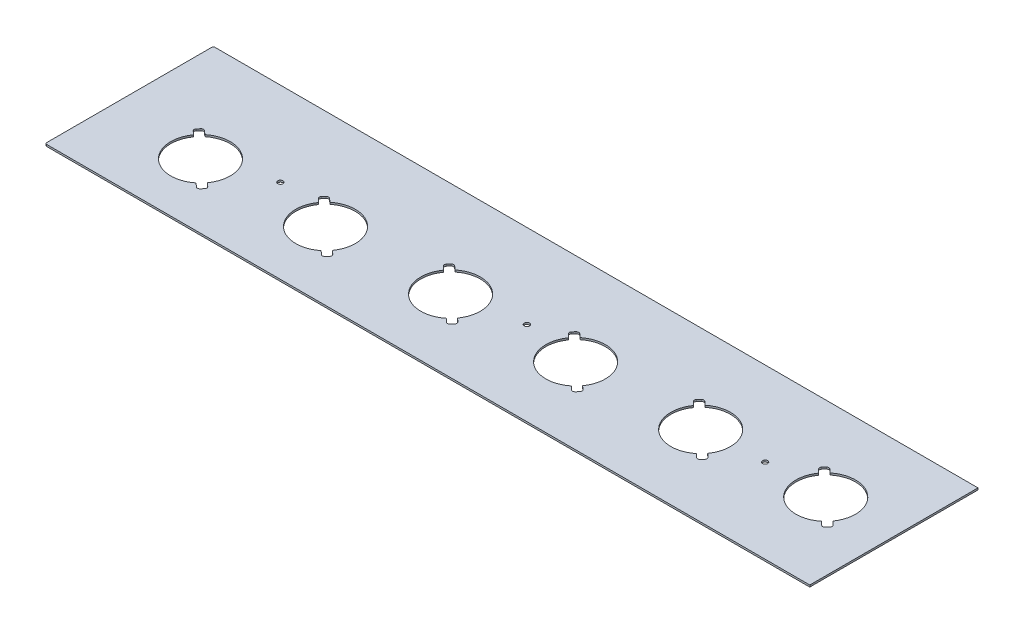
SolidWorks part; units mm, degrees
material "E-Glass Fiber"
ref_plane "Front" through (0, 0, 0) normal (0, 0, 1) x (1, 0, 0)
ref_plane "Top" through (0, 0, 0) normal (0, 1, 0) x (1, 0, 0)
ref_plane "Right" through (0, 0, 0) normal (1, 0, 0) x (0, 0, -1)
sketch "Sketch2" plane through (0, 0, 0) normal (0, 1, 0) x (1, 0, 0)
  line L1 (-317.5, 69.85) -> (317.5, 69.85)
  line L2 (-317.5, 69.85) -> (-317.5, -69.85)
  line L3 (-317.5, -69.85) -> (317.5, -69.85)
  line L5 (317.5, 69.85) -> (317.5, -69.85)
  line L6 (-317.5, 69.85) -> (317.5, -69.85) construction
  line L13 (180.6816, -17.7581) -> (183.4178, -20.3225) construction
  line L14 (183.5094, -23.1494) -> (181.6631, -25.1194) construction
  line L18 (178.8362, -25.2111) -> (176.1, -22.6468) construction
  line L19 (141.7919, 18.6889) -> (144.5281, 16.1246) construction
  line L20 (139.9465, 11.2359) -> (137.2103, 13.8003) construction
  line L24 (137.1187, 16.6272) -> (138.965, 18.5973) construction
  line L25 (180.4711, -17.5609) -> (183.4178, -20.3225)
  line L30 (183.5094, -23.1494) -> (181.6631, -25.1194)
  line L31 (178.8362, -25.2111) -> (175.8895, -22.4495)
  line L32 (141.7919, 18.6889) -> (144.7386, 15.9274)
  line L36 (140.157, 11.0387) -> (137.2103, 13.8003)
  line L37 (137.1187, 16.6272) -> (138.965, 18.5973)
  line L38 (39.3646, 7.9749) -> (36.6284, 10.5392) construction
  line L42 (242.3739, 21.95) -> (245.1101, 19.3857) construction
  line L43 (237.7006, 19.8883) -> (239.547, 21.8584) construction
  line L44 (240.5285, 14.497) -> (237.7923, 17.0614) construction
  line L45 (242.3739, 21.95) -> (245.3205, 19.1884)
  line L46 (237.7006, 19.8883) -> (239.547, 21.8584)
  line L47 (240.7389, 14.2998) -> (237.7923, 17.0614)
  line L48 (281.2635, -14.497) -> (283.9997, -17.0614) construction
  line L49 (284.0914, -19.8883) -> (282.245, -21.8584) construction
  line L50 (279.4181, -21.95) -> (276.6819, -19.3857) construction
  line L51 (281.0531, -14.2998) -> (283.9997, -17.0614)
  line L52 (284.0914, -19.8883) -> (282.245, -21.8584)
  line L53 (279.4181, -21.95) -> (276.4715, -19.1884)
  line L78 (36.5367, 13.3661) -> (38.3831, 15.3362) construction
  line L79 (41.21, 15.4278) -> (43.9462, 12.8635) construction
  line L80 (80.0996, -21.0192) -> (82.8358, -23.5835) construction
  line L81 (82.9275, -26.4105) -> (81.0811, -28.3805) construction
  line L82 (78.2542, -28.4722) -> (75.518, -25.9079) construction
  line L83 (39.575, 7.7776) -> (36.6284, 10.5392)
  line L84 (36.5367, 13.3661) -> (38.3831, 15.3362)
  line L85 (41.21, 15.4278) -> (44.1566, 12.6663)
  line L86 (79.8892, -20.822) -> (82.8358, -23.5835)
  line L87 (82.9275, -26.4105) -> (81.0811, -28.3805)
  line L88 (78.2542, -28.4722) -> (75.3076, -25.7106)
  line L89 (-61.2174, 4.7138) -> (-63.9536, 7.2781) construction
  line L90 (-64.0452, 10.105) -> (-62.1989, 12.0751) construction
  line L91 (-59.3719, 12.1668) -> (-56.6358, 9.6024) construction
  line L92 (-20.4823, -24.2803) -> (-17.7461, -26.8446) construction
  line L93 (-17.6545, -29.6716) -> (-19.5008, -31.6416) construction
  line L94 (-22.3277, -31.7333) -> (-25.0639, -29.1689) construction
  line L95 (-61.0069, 4.5165) -> (-63.9536, 7.2781)
  line L96 (-64.0452, 10.105) -> (-62.1989, 12.0751)
  line L97 (-59.3719, 12.1668) -> (-56.4253, 9.4052)
  line L98 (-20.6928, -24.0831) -> (-17.7461, -26.8446)
  line L99 (-17.6545, -29.6716) -> (-19.5008, -31.6416)
  line L100 (-22.3277, -31.7333) -> (-25.2744, -28.9717)
  line L101 (-161.7993, 1.4527) -> (-164.5355, 4.017) construction
  line L102 (-164.6272, 6.844) -> (-162.7808, 8.814) construction
  line L103 (-159.9539, 8.9057) -> (-157.2177, 6.3413) construction
  line L104 (-121.0643, -27.5414) -> (-118.3281, -30.1057) construction
  line L105 (-118.2364, -32.9326) -> (-120.0827, -34.9027) construction
  line L106 (-122.9097, -34.9944) -> (-125.6459, -32.43) construction
  line L107 (-161.5889, 1.2555) -> (-164.5355, 4.017)
  line L108 (-164.6272, 6.844) -> (-162.7808, 8.814)
  line L109 (-159.9539, 8.9057) -> (-157.0073, 6.1441)
  line L110 (-121.2747, -27.3441) -> (-118.3281, -30.1057)
  line L111 (-118.2364, -32.9326) -> (-120.0827, -34.9027)
  line L112 (-122.9097, -34.9944) -> (-125.8563, -32.2328)
  line L113 (-221.6462, -30.8025) -> (-218.91, -33.3668) construction
  line L114 (-218.8184, -36.1937) -> (-220.6647, -38.1638) construction
  line L115 (-223.4916, -38.2554) -> (-226.2278, -35.6911) construction
  line L116 (-260.5358, 5.6446) -> (-257.7997, 3.0803) construction
  line L117 (-265.2091, 3.5829) -> (-263.3628, 5.5529) construction
  line L118 (-262.3813, -1.8084) -> (-265.1174, 0.7559) construction
  line L119 (-221.8567, -30.6052) -> (-218.91, -33.3668)
  line L120 (-218.8184, -36.1937) -> (-220.6647, -38.1638)
  line L121 (-223.4916, -38.2554) -> (-226.4383, -35.4939)
  line L122 (-260.5358, 5.6446) -> (-257.5892, 2.883)
  line L123 (-265.2091, 3.5829) -> (-263.3628, 5.5529)
  line L124 (-262.1708, -2.0056) -> (-265.1174, 0.7559)
  arc A16 (183.5094, -23.1494) -> (183.4178, -20.3225) centre (182.0501, -21.7817) ccw construction
  arc A20 (178.8362, -25.2111) -> (181.6631, -25.1194) centre (180.2038, -23.7518) ccw construction
  arc A24 (141.7919, 18.6889) -> (138.965, 18.5973) centre (140.4243, 17.2296) ccw construction
  arc A28 (137.1187, 16.6272) -> (137.2103, 13.8003) centre (138.578, 15.2596) ccw construction
  arc A45 (183.5094, -23.1494) -> (183.4178, -20.3225) centre (182.0501, -21.7817) ccw
  arc A46 (178.8362, -25.2111) -> (181.6631, -25.1194) centre (180.2038, -23.7518) ccw
  arc A47 (240.7389, 14.2998) -> (276.4715, -19.1884) centre (260.896, 0) ccw
  arc A48 (242.3739, 21.95) -> (239.547, 21.8584) centre (241.0063, 20.4907) ccw construction
  arc A49 (237.7006, 19.8883) -> (237.7923, 17.0614) centre (239.1599, 18.5207) ccw construction
  arc A50 (242.3739, 21.95) -> (239.547, 21.8584) centre (241.0063, 20.4907) ccw
  arc A51 (237.7006, 19.8883) -> (237.7923, 17.0614) centre (239.1599, 18.5207) ccw
  arc A52 (284.0914, -19.8883) -> (283.9997, -17.0614) centre (282.6321, -18.5207) ccw construction
  arc A53 (279.4181, -21.95) -> (282.245, -21.8584) centre (280.7857, -20.4907) ccw construction
  arc A54 (284.0914, -19.8883) -> (283.9997, -17.0614) centre (282.6321, -18.5207) ccw
  arc A55 (279.4181, -21.95) -> (282.245, -21.8584) centre (280.7857, -20.4907) ccw
  arc A56 (281.0531, -14.2998) -> (245.3205, 19.1884) centre (260.896, 0) ccw
  arc A79 (141.7919, 18.6889) -> (138.965, 18.5973) centre (140.4243, 17.2296) ccw
  arc A80 (137.1187, 16.6272) -> (137.2103, 13.8003) centre (138.578, 15.2596) ccw
  arc A81 (180.4711, -17.5609) -> (144.7386, 15.9274) centre (160.3141, -3.2611) ccw
  arc A82 (140.157, 11.0387) -> (175.8895, -22.4495) centre (160.3141, -3.2611) ccw
  arc A83 (36.5367, 13.3661) -> (36.6284, 10.5392) centre (37.996, 11.9985) ccw construction
  arc A84 (41.21, 15.4278) -> (38.3831, 15.3362) centre (39.8424, 13.9685) ccw construction
  arc A85 (82.9275, -26.4105) -> (82.8358, -23.5835) centre (81.4682, -25.0428) ccw construction
  arc A86 (78.2542, -28.4722) -> (81.0811, -28.3805) centre (79.6219, -27.0129) ccw construction
  arc A87 (36.5367, 13.3661) -> (36.6284, 10.5392) centre (37.996, 11.9985) ccw
  arc A88 (41.21, 15.4278) -> (38.3831, 15.3362) centre (39.8424, 13.9685) ccw
  arc A89 (82.9275, -26.4105) -> (82.8358, -23.5835) centre (81.4682, -25.0428) ccw
  arc A90 (78.2542, -28.4722) -> (81.0811, -28.3805) centre (79.6219, -27.0129) ccw
  arc A91 (-64.0452, 10.105) -> (-63.9536, 7.2781) centre (-62.5859, 8.7374) ccw construction
  arc A92 (-59.3719, 12.1668) -> (-62.1989, 12.0751) centre (-60.7396, 10.7075) ccw construction
  arc A93 (-17.6545, -29.6716) -> (-17.7461, -26.8446) centre (-19.1138, -28.3039) ccw construction
  arc A94 (-22.3277, -31.7333) -> (-19.5008, -31.6416) centre (-20.9601, -30.274) ccw construction
  arc A95 (-64.0452, 10.105) -> (-63.9536, 7.2781) centre (-62.5859, 8.7374) ccw
  arc A96 (-59.3719, 12.1668) -> (-62.1989, 12.0751) centre (-60.7396, 10.7075) ccw
  arc A97 (-17.6545, -29.6716) -> (-17.7461, -26.8446) centre (-19.1138, -28.3039) ccw
  arc A98 (-22.3277, -31.7333) -> (-19.5008, -31.6416) centre (-20.9601, -30.274) ccw
  arc A99 (-164.6272, 6.844) -> (-164.5355, 4.017) centre (-163.1679, 5.4763) ccw construction
  arc A100 (-159.9539, 8.9057) -> (-162.7808, 8.814) centre (-161.3215, 7.4464) ccw construction
  arc A101 (-118.2364, -32.9326) -> (-118.3281, -30.1057) centre (-119.6957, -31.565) ccw construction
  arc A102 (-122.9097, -34.9944) -> (-120.0827, -34.9027) centre (-121.542, -33.5351) ccw construction
  arc A103 (-164.6272, 6.844) -> (-164.5355, 4.017) centre (-163.1679, 5.4763) ccw
  arc A104 (-159.9539, 8.9057) -> (-162.7808, 8.814) centre (-161.3215, 7.4464) ccw
  arc A105 (-118.2364, -32.9326) -> (-118.3281, -30.1057) centre (-119.6957, -31.565) ccw
  arc A106 (-122.9097, -34.9944) -> (-120.0827, -34.9027) centre (-121.542, -33.5351) ccw
  arc A107 (-218.8184, -36.1937) -> (-218.91, -33.3668) centre (-220.2777, -34.8261) ccw construction
  arc A108 (-223.4916, -38.2554) -> (-220.6647, -38.1638) centre (-222.124, -36.7961) ccw construction
  arc A109 (-260.5358, 5.6446) -> (-263.3628, 5.5529) centre (-261.9035, 4.1853) ccw construction
  arc A110 (-265.2091, 3.5829) -> (-265.1174, 0.7559) centre (-263.7498, 2.2152) ccw construction
  arc A111 (-218.8184, -36.1937) -> (-218.91, -33.3668) centre (-220.2777, -34.8261) ccw
  arc A112 (-223.4916, -38.2554) -> (-220.6647, -38.1638) centre (-222.124, -36.7961) ccw
  arc A113 (-260.5358, 5.6446) -> (-263.3628, 5.5529) centre (-261.9035, 4.1853) ccw
  arc A114 (-265.2091, 3.5829) -> (-265.1174, 0.7559) centre (-263.7498, 2.2152) ccw
  arc A115 (79.8892, -20.822) -> (44.1566, 12.6663) centre (59.7321, -6.5222) ccw
  arc A116 (-20.6928, -24.0831) -> (-56.4253, 9.4052) centre (-40.8498, -9.7833) ccw
  arc A117 (-121.2747, -27.3441) -> (-157.0073, 6.1441) centre (-141.4318, -13.0443) ccw
  arc A118 (-221.8567, -30.6052) -> (-257.5892, 2.883) centre (-242.0137, -16.3054) ccw
  arc A119 (-262.1708, -2.0056) -> (-226.4383, -35.4939) centre (-242.0137, -16.3054) ccw
  arc A120 (-161.5889, 1.2555) -> (-125.8563, -32.2328) centre (-141.4318, -13.0443) ccw
  arc A121 (-61.0069, 4.5165) -> (-25.2744, -28.9717) centre (-40.8498, -9.7833) ccw
  arc A122 (39.575, 7.7776) -> (75.3076, -25.7106) centre (59.7321, -6.5222) ccw
  point P0 (0, 0)
  dimension "D3" = 24.7142
  dimension "D1" = 635
  dimension "D2" = 139.7
extrude "Boss-Extrude1" add sketch "Sketch2" along normal blind 1.524
sketch "Sketch3" [suppressed] plane through (0, 1.524, 0) normal (0, 1, 0) x (1, 0, 0)
  line L42 (-317.5, -69.85) -> (-292.1, -69.85) construction
  line L43 (285.896, 0) -> (287.166, 0)
  line L44 (-317.5, 69.85) -> (-317.5, -69.85) construction
  line L45 (-317.5, 49.8475) -> (-317.5, 69.85) construction
  line L46 (260.896, -26.27) -> (260.896, 26.27) construction
  line L47 (-292.1, -69.85) -> (-292.1, 69.85)
  line L48 (-292.1, 49.8475) -> (-317.5, 49.8475)
  line L49 (234.626, 26.27) -> (287.166, 26.27) construction
  line L50 (-292.1, -49.8475) -> (-317.5, -49.8475)
  line L51 (-317.5, -49.8475) -> (-317.5, -69.85) construction
  line L52 (287.166, 0) -> (287.166, -26.27)
  line L53 (287.166, 0) -> (234.626, 0) construction
  line L54 (234.626, -26.27) -> (234.626, 26.27) construction
  line L55 (260.896, 26.27) -> (234.626, 26.27)
  line L57 (234.626, 26.27) -> (234.626, 0)
  line L58 (234.626, 0) -> (235.896, 0)
  line L59 (260.896, 26.27) -> (260.896, 25)
  line L61 (287.166, -26.27) -> (260.896, -26.27)
  line L63 (260.896, -26.27) -> (260.896, -25)
  line L64 (160.261, -26.27) -> (160.261, 26.27) construction
  line L65 (133.991, 26.27) -> (186.531, 26.27) construction
  line L67 (186.531, -26.27) -> (133.991, -26.27) construction
  line L68 (186.531, 0) -> (133.991, 0) construction
  line L69 (133.991, -26.27) -> (133.991, 26.27) construction
  line L70 (160.261, 26.27) -> (133.991, 26.27)
  line L71 (133.991, 26.27) -> (133.991, 0)
  line L72 (133.991, 0) -> (135.261, 0)
  line L73 (160.261, 26.27) -> (160.261, 25)
  line L74 (185.261, 0) -> (186.531, 0)
  line L75 (186.531, 0) -> (186.531, -26.27)
  line L76 (186.531, -26.27) -> (160.261, -26.27)
  line L77 (160.261, -26.27) -> (160.261, -25)
  line L78 (59.626, -26.27) -> (59.626, 26.27) construction
  line L79 (33.356, 26.27) -> (85.896, 26.27) construction
  line L81 (85.896, -26.27) -> (33.356, -26.27) construction
  line L82 (85.896, 0) -> (33.356, 0) construction
  line L83 (33.356, -26.27) -> (33.356, 26.27) construction
  line L85 (59.626, 25) -> (59.626, 26.27)
  line L86 (59.626, 26.27) -> (33.356, 26.27)
  line L87 (33.356, 26.27) -> (33.356, 0)
  line L88 (33.356, 0) -> (34.626, 0)
  line L90 (84.626, 0) -> (85.896, 0)
  line L92 (85.896, 0) -> (85.896, -26.27)
  line L93 (85.896, -26.27) -> (59.626, -26.27)
  line L94 (59.626, -26.27) -> (59.626, -25)
  line L96 (-292.1, 49.5863) -> (-292.1, 88.9) construction
  line L97 (317.5, 69.85) -> (-317.5, 69.85) construction
  line L98 (-317.5, -69.85) -> (317.5, -69.85) construction
  line L99 (317.5, 69.85) -> (-317.5, 69.85) construction
  arc A24 (241.009, 15.1494) -> (276.0454, -19.887) centre (260.896, 0) ccw construction
  arc A25 (280.783, -15.1494) -> (245.7466, 19.887) centre (260.896, 0) ccw construction
  arc A26 (140.374, 15.1494) -> (175.4104, -19.887) centre (160.261, 0) ccw construction
  arc A27 (180.148, -15.1494) -> (145.1116, 19.887) centre (160.261, 0) ccw construction
  point P8 (260.896, 0)
  point P16 (160.261, 0)
  point P17 (260.896, 0)
  point P37 (160.261, 0)
  point P52 (59.626, 0)
  point P60 (59.626, 0)
  dimension "D1" = 20.0025
fillet "Fillet1" radius 1.27 2 edges at (-317.5, 0.762, 69.85) (-317.5, 0.762, -69.85)
hole_wizard "#8 Clearance Hole1" positions "Sketch4" profile "Sketch5" hole size "#8" standard "ANSI Inch" end condition through all
sketch "Sketch4" plane through (0, 1.524, 0) normal (0, 1, 0) x (1, 0, 0)
  point P0 (210.5786, 0)
  point P3 (12.7, 0)
  point P6 (-191.9606, 0)
sketch "Sketch5" plane through (210.5786, 1.524, 0) normal (1, 0, 0) x (0, 0, 1)
  line L0 (0, 0) -> (0, 1.524)
  line L1 (0, 1.524) -> (2.1526, 1.524)
  line L2 (2.1526, 1.524) -> (2.1526, 0)
  line L5 (2.1526, 0) -> (0, 0)
  line L11 (0, -6.35) -> (0, 107.95) construction
  dimension "Thru Hole Dia." = 4.3053
  dimension "Thru Hole Depth" = 1.524
